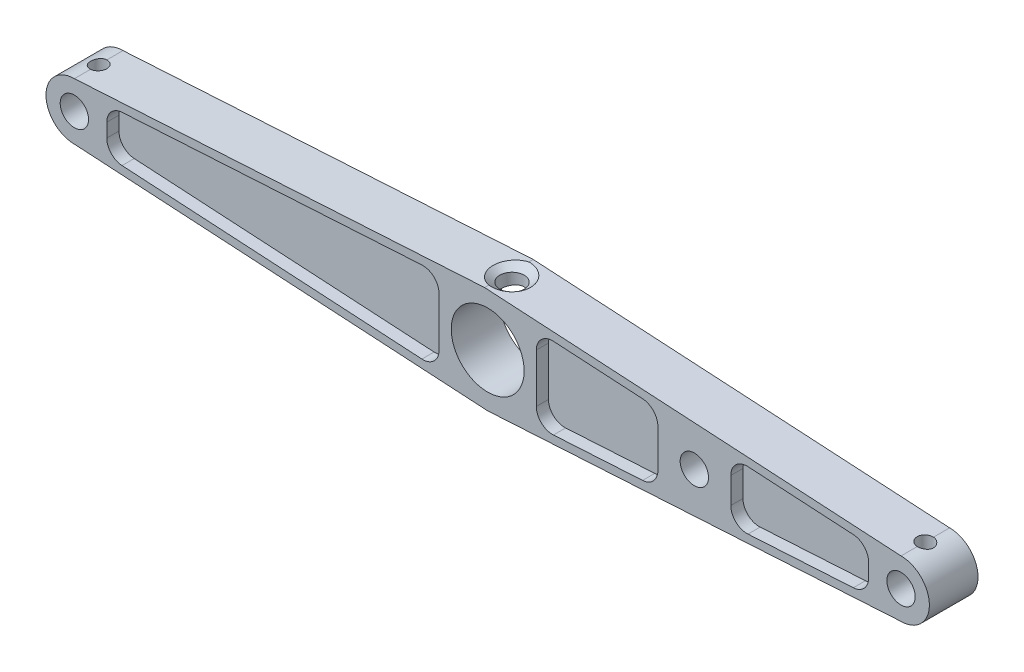
SolidWorks part; units mm, degrees
ref_plane "Front Plane" through (0, 0, 0) normal (0, 0, 1) x (1, 0, 0)
ref_plane "Top Plane" through (0, 0, 0) normal (0, 1, 0) x (1, 0, 0)
ref_plane "Right Plane" through (0, 0, 0) normal (1, 0, 0) x (0, 0, -1)
sketch "Sketch1" plane through (0, 0, 0) normal (0, 0, 1) x (1, 0, 0)
  line L0 (51, 0) -> (-51, 0) construction
  line L1 (0, 40.2707) -> (0, -31.9758) construction
  line L2 (0, -6.5) -> (-51, -3.5)
  line L3 (0, -6.5) -> (51, -3.5)
  line L4 (-51, 3.5) -> (-0.3831, 6.4887)
  line L5 (-0.3831, 6.4887) -> (51, 3.5)
  circle A0 centre (-51, 0) radius 1.75
  circle A1 centre (51, 0) radius 1.75
  arc A2 (-51, 3.5) -> (-51, -3.5) centre (-51, 0) ccw
  arc A3 (51, -3.5) -> (51, 3.5) centre (51, 0) ccw
  circle A4 centre (0, 0) radius 3
  circle A5 centre (0, 0) radius 4.5
  point P3 (-50.9411, 2.5017)
  point P4 (0, 0)
  point P10 (-0.3827, 5.487)
  point P20 (50.9419, 2.5017)
  point P22 (0, -5.4983)
  point P23 (50.9413, -2.5017)
  point P24 (-50.9413, -2.5017)
  point P32 (0, 0)
extrude "Boss-Extrude1" add sketch "Sketch1" along normal blind 6 contours L3 A3 L5 L4 A2 L2 A5 A0 A1
sketch "Sketch2" plane through (0, 0, 6) normal (0, 0, 1) x (1, 0, 0)
  line L0 (50.9419, 2.5017) -> (-0.3827, 5.487)
  line L1 (-8.1179, 5.0303) -> (-45.1179, 2.8456)
  line L2 (-45.1174, -2.8443) -> (-8.1174, -5.0208)
  line L3 (0, -5.4983) -> (50.9413, -2.5017)
  line L12 (0, 0) -> (0, -13.2007) construction
  line L13 (0, 0) -> (0, 16.145) construction
  line L14 (0, 0) -> (-47, 0) construction
  line L15 (-47, 0.849) -> (-47, -0.8478)
  line L17 (-6, 3.0337) -> (-6, -3.0242)
  arc A0 (-6, -3.0242) -> (-8.1174, -5.0208) centre (-8, -3.0242) cw
  arc A1 (-8.1179, 5.0303) -> (-6, 3.0337) centre (-8, 3.0337) cw
  arc A6 (-45.1174, -2.8443) -> (-47, -0.8478) centre (-45, -0.8478) cw
  arc A7 (-45.1179, 2.8456) -> (-47, 0.849) centre (-45, 0.849) ccw
  dimension "D1" = 2
extrude "Cut-Extrude1" cut sketch "Sketch2" against normal blind 1.5 contours L1 A7 L15 A6 L2 A0 L17 A1
pattern_linear "LPattern1" count 2 spacing 4.5 along (0, 0, -1) of "Cut-Extrude1"
sketch "Sketch3" plane through (0, 0, 6) normal (0, 0, 1) x (1, 0, 0)
  line L0 (0, -6.5) -> (51, -3.5) construction
  line L1 (-0.3831, 6.4887) -> (51, 3.5) construction
  line L2 (6, -6.1471) -> (51, -3.5)
  line L3 (-0.3831, 6.4887) -> (0, 6.4664)
  line L4 (-0.4412, 5.4904) -> (0, 5.4647)
  line L5 (-0.0587, -5.5017) -> (0, -5.4983)
  line L6 (0, 9.6333) -> (0, -9.6333)
  line L7 (0, 8.2066) -> (6, 8.2066)
  line L8 (6, 2.996) -> (6, -3.0242)
  line L9 (8.1161, 4.9926) -> (19.1161, 4.3528)
  line L10 (6, 6.1174) -> (51, 3.5)
  line L11 (-0.4412, 5.4904) -> (50.9419, 2.5017) construction
  line L12 (8.1174, -5.0208) -> (19.1174, -4.3737)
  line L13 (-0.3831, 6.4887) -> (51, 3.5) construction
  line L14 (6, 8.2066) -> (21, 8.2066)
  line L15 (-0.0587, -5.5017) -> (50.9413, -2.5017) construction
  line L16 (0, -6.5) -> (51, -3.5) construction
  line L17 (21, 2.3562) -> (21, -2.3772)
  arc A0 (21, -2.3772) -> (19.1174, -4.3737) centre (19, -2.3772) cw
  arc A1 (21, 2.3562) -> (19.1161, 4.3528) centre (19, 2.3562) ccw
  arc A2 (6, -3.0242) -> (8.1174, -5.0208) centre (8, -3.0242) ccw
  arc A3 (8.1161, 4.9926) -> (6, 2.996) centre (8, 2.996) ccw
  point P12 (0, 0)
  dimension "D3" = 2
  dimension "D1" = 1
  dimension "D2" = 1
extrude "Cut-Extrude2" cut sketch "Sketch3" against normal blind 1.5 contours L9 A3 L8 A2 L12 A0 L17 A1
pattern_linear "LPattern2" count 2 spacing 4.5 along (0, 0, -1) of "Cut-Extrude2"
sketch "Sketch4" plane through (0, 0, 6) normal (0, 0, 1) x (1, 0, 0)
  line L0 (0, 0) -> (0, 17.1543) construction
  line L1 (0, -6.5) -> (51, -3.5) construction
  line L2 (-0.3831, 6.4887) -> (51, 3.5) construction
  line L3 (0, -6.5) -> (51, -3.5)
  line L4 (-0.3831, 6.4887) -> (51, 3.5)
  line L5 (-0.4412, 5.4904) -> (0, 5.4647)
  line L6 (32.1174, -3.609) -> (45.1174, -2.8443)
  line L7 (0, 10.775) -> (47, 10.775)
  line L8 (30, 1.6001) -> (30, -1.6125)
  line L9 (32.1161, 3.5967) -> (45.1161, 2.8405)
  line L10 (47, 0.8439) -> (47, -0.8478)
  line L11 (-0.4412, 5.4904) -> (50.9419, 2.5017) construction
  line L12 (-0.0587, -5.5017) -> (50.9413, -2.5017) construction
  arc A0 (32.1174, -3.609) -> (30, -1.6125) centre (32, -1.6125) cw
  arc A1 (32.1161, 3.5967) -> (30, 1.6001) centre (32, 1.6001) ccw
  arc A2 (45.1174, -2.8443) -> (47, -0.8478) centre (45, -0.8478) ccw
  arc A3 (47, 0.8439) -> (45.1161, 2.8405) centre (45, 0.8439) ccw
  dimension "D4" = 2
  dimension "D5" = 2
  dimension "D3" = 47
  dimension "D1" = 1
  dimension "D2" = 1
extrude "Cut-Extrude3" cut sketch "Sketch4" against normal blind 1.5 contours L10 A3 L9 A1 L8 A0 L6 A2
pattern_linear "LPattern3" count 2 spacing 4.5 along (0, 0, -1) of "Cut-Extrude3"
sketch "Sketch5" plane through (0, 0, 6) normal (0, 0, 1) x (1, 0, 0)
  circle A0 centre (25.5, 0) radius 1.75
extrude "Cut-Extrude4" cut sketch "Sketch5" against normal blind 11.5
ref_plane "Plane1" through (0, 6.4887, 0) normal (0, 1, 0) x (1, 0, 0)
sketch "Sketch7" plane through (0, 0, 0) normal (1, 0, 0) x (0, 0, -1)
  line L0 (-3, 6.4887) -> (-5.5, 6.4887)
  line L1 (-6, 6.4887) -> (0, 6.4887) construction
  line L2 (-3, 6.4887) -> (-3, 5.7574)
  line L3 (-4.5, 2.3017) -> (-3, 2.3017)
  line L4 (-4.5, 5.7574) -> (-4.5, 2.3017)
  line L5 (-3, 2.3017) -> (-3, 5.7574)
  line L6 (-5.5, 6.4887) -> (-4.5, 5.7574)
revolve "Cut-Revolve1" cut sketch "Sketch7" angle 360 about L5
sketch "Sketch8" plane through (0, 6.4887, 0) normal (0, 1, 0) x (1, 0, 0)
  line L0 (-51, -6) -> (-51, 0) construction
  line L1 (51, -6) -> (51, 0) construction
  circle A0 centre (-51, -3) radius 1
  circle A1 centre (51, -3) radius 1
extrude "Cut-Extrude5" cut sketch "Sketch8" against normal blind 7
